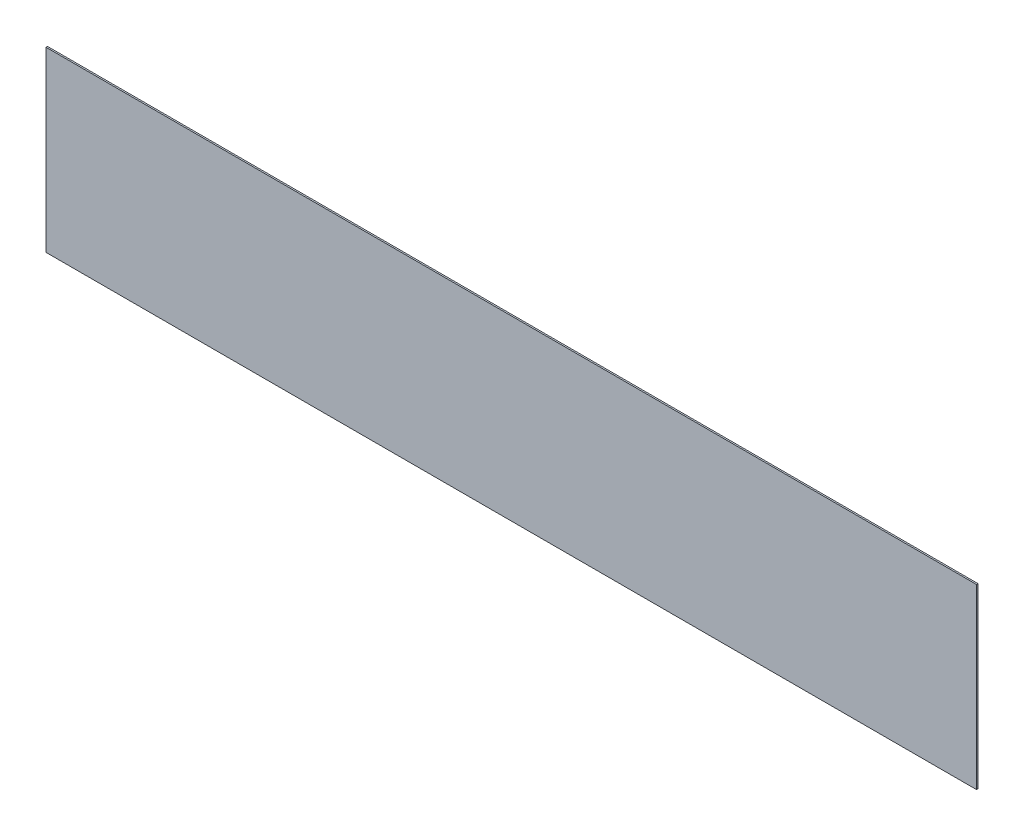
SolidWorks part; units mm, degrees
ref_plane "Front Plane" through (0, 0, 0) normal (0, 0, 1) x (1, 0, 0)
ref_plane "Top Plane" through (0, 0, 0) normal (0, 1, 0) x (1, 0, 0)
ref_plane "Right Plane" through (0, 0, 0) normal (1, 0, 0) x (0, 0, -1)
other "Configuration Table"
sketch "Sketch1" plane through (0, 0, 0) normal (0, 0, 1) x (1, 0, 0)
  line L1 (0, 0) -> (618, 0)
  line L2 (0, 0) -> (0, 118)
  line L3 (0, 118) -> (618, 118)
  line L4 (618, 0) -> (618, 118)
extrude "CEK_icecek_on_ic_sac_1.0_1" add sketch "Sketch1" along normal blind 1 separate body
